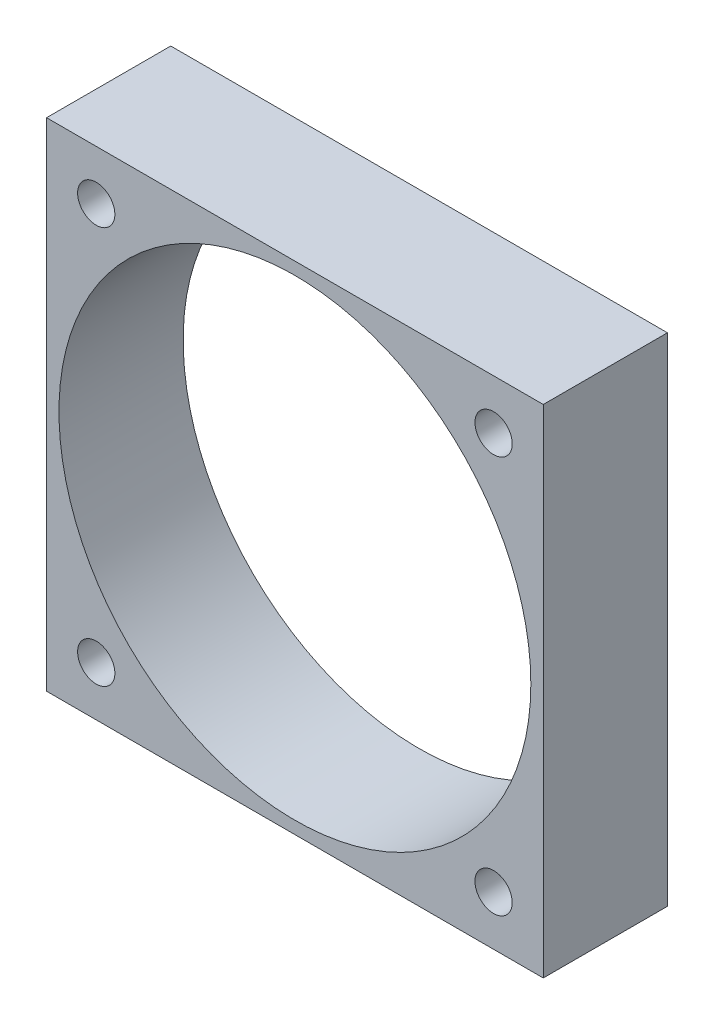
SolidWorks part; units mm, degrees
ref_plane "Plano frontal" through (0, 0, 0) normal (0, 0, 1) x (1, 0, 0)
ref_plane "Plano superior" through (0, 0, 0) normal (0, 1, 0) x (1, 0, 0)
ref_plane "Plano direito" through (0, 0, 0) normal (1, 0, 0) x (0, 0, -1)
sketch "Esboço1" plane through (0, 0, 0) normal (0, 0, 1) x (1, 0, 0)
  line L1 (-20, -20) -> (20, -20)
  line L2 (-20, -20) -> (-20, 20)
  line L3 (-20, 20) -> (20, 20)
  line L4 (20, -20) -> (20, 20)
  line L5 (-20, -20) -> (20, 20) construction
  line L6 (-20, 20) -> (20, -20) construction
  line L11 (-16, -16) -> (16, 16) construction
  line L12 (-16, 16) -> (16, -16) construction
  circle A0 centre (-16, 16) radius 1.5
  circle A1 centre (16, 16) radius 1.5
  circle A2 centre (-16, -16) radius 1.5
  circle A3 centre (16, -16) radius 1.5
  circle A4 centre (0, 0) radius 19
  point P0 (0, 0)
  point P6 (0, 0)
extrude "Ressalto-extrusão1" add sketch "Esboço1" along normal blind 10
